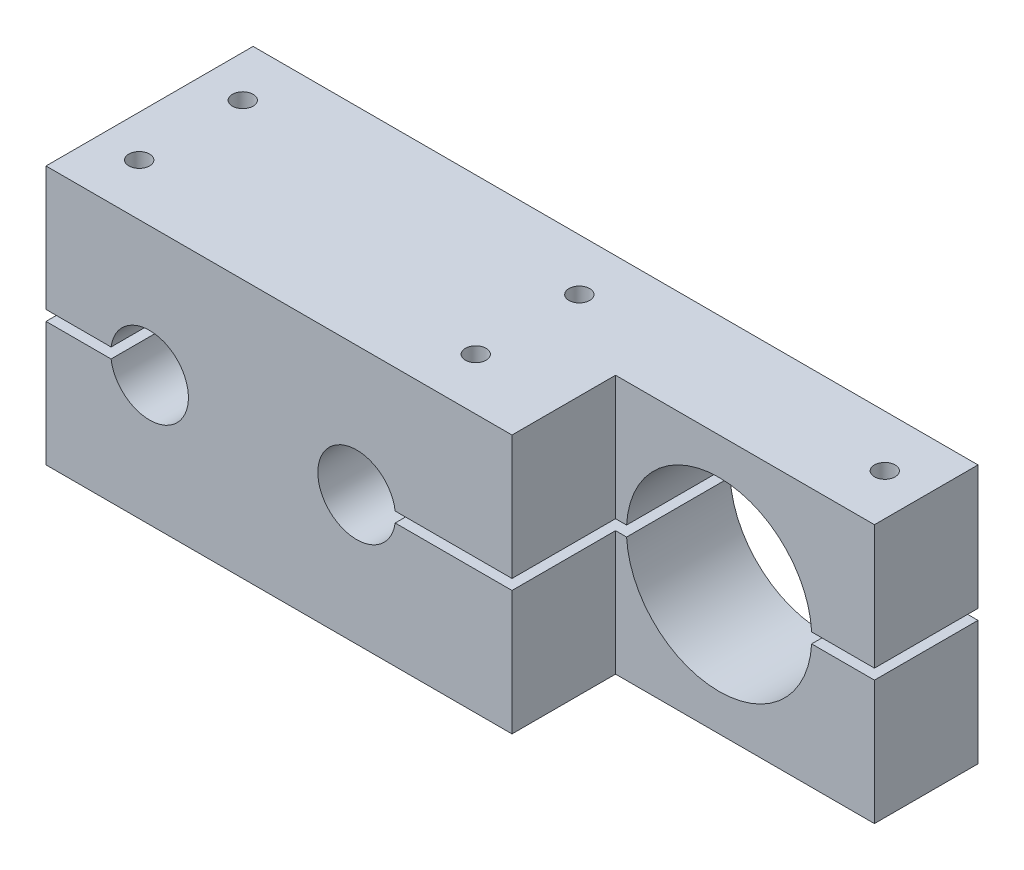
SolidWorks part; units mm, degrees
material "Сосна"
ref_plane "Спереди" through (0, 0, 0) normal (0, 0, 1) x (1, 0, 0)
ref_plane "Сверху" through (0, 0, 0) normal (0, 1, 0) x (1, 0, 0)
ref_plane "Справа" through (0, 0, 0) normal (1, 0, 0) x (0, 0, -1)
sketch "Эскиз1" plane through (0, 0, 0) normal (0, 0, 1) x (1, 0, 0)
  line L0 (67.4329, 26.0009) -> (92.128, 26.0009)
  line L1 (0, 0) -> (140, 0)
  line L2 (0, 0) -> (0, 24)
  line L3 (0, 50) -> (140, 50)
  line L4 (140, 50) -> (140, 26.0009)
  line L5 (67.4329, 23.9991) -> (92.128, 23.9991)
  line L6 (0, 26) -> (12.567, 26)
  line L7 (127.872, 26.0009) -> (140, 26.0009)
  line L8 (0, 24) -> (12.567, 24)
  line L9 (0, 26) -> (0, 50)
  line L10 (127.872, 23.9991) -> (140, 23.9991)
  line L11 (140, 23.9991) -> (140, 0)
  arc A0 (12.567, 24) -> (12.567, 26) centre (20, 25) ccw
  arc A1 (67.4329, 26.0009) -> (67.4329, 23.9991) centre (60, 25) ccw
  arc A2 (92.128, 23.9991) -> (127.872, 23.9991) centre (110, 25) ccw
  arc A3 (127.872, 26.0009) -> (92.128, 26.0009) centre (110, 25) ccw
  dimension "D5" = 40
  dimension "D4" = 25
  dimension "D6" = 17.9
  dimension "D8" = 7.5
  dimension "D9" = 7.5
  dimension "D12" = 17.9
  dimension "D1" = 140
  dimension "D2" = 50
  dimension "D3" = 20
  dimension "D7" = 30
  dimension "D10" = 25
  dimension "D11" = 25
  dimension "D13" = 140
extrude "Бобышка-Вытянуть1" add sketch "Эскиз1" along normal blind 40
sketch "Эскиз8" plane through (0, 0, 0) normal (0, -1, 0) x (1, 0, 0)
  line L0 (0, 40) -> (0, 0) construction
  line L1 (0, 40) -> (140, 40) construction
  line L2 (0, 0) -> (140, 0) construction
  line L3 (140, 40) -> (140, 0) construction
  line L5 (0, 0) -> (140, 0) construction
  line L6 (140, 20) -> (90, 20)
  line L7 (0, 40) -> (140, 40) construction
  line L8 (140, 20) -> (90, 20)
  line L9 (140, 20) -> (140, 40)
  line L10 (140, 40) -> (90, 40)
  line L11 (90, 20) -> (90, 40)
  line L13 (0, 40) -> (140, 40)
  line L14 (0, 40) -> (0, 0)
  line L15 (0, 0) -> (140, 0)
  line L16 (140, 40) -> (140, 0)
  circle A0 centre (8, 30) radius 2
  circle A1 centre (8, 10) radius 2
  circle A2 centre (132, 10) radius 2
  circle A4 centre (73, 30) radius 2
  circle A5 centre (73, 10) radius 2
  dimension "D1" = 8
  dimension "D3" = 10
  dimension "D5" = 65
  dimension "D6" = 65
  dimension "D7" = 8
  dimension "D2" = 10
  dimension "D4" = 8
  dimension "D8" = 10
  dimension "D9" = 20
  dimension "D10" = 50
extrude "Вырез-Вытянуть1" cut sketch "Эскиз8" against normal blind 50 contours A2 | A4 | A0 | A1 | L6 L11 L10 L9 | A5
